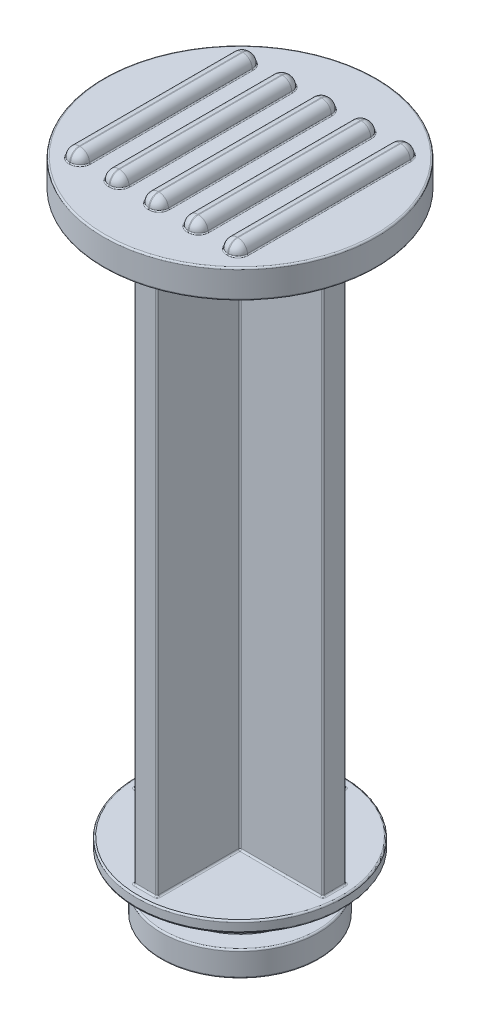
SolidWorks part; units mm, degrees
material "PET"
ref_plane "Front Plane" through (0, 0, 0) normal (0, 0, 1) x (1, 0, 0)
ref_plane "Top Plane" through (0, 0, 0) normal (0, 1, 0) x (1, 0, 0)
ref_plane "Right Plane" through (0, 0, 0) normal (1, 0, 0) x (0, 0, -1)
sketch "Main Body Sketch" plane through (0, 0, 0) normal (0, 0, 1) x (1, 0, 0)
  line L1 (-9, -26.665) -> (9, -26.665)
  line L2 (-9, -26.665) -> (-9, 26.665)
  line L3 (-9, 26.665) -> (9, 26.665)
  line L4 (9, -26.665) -> (9, 26.665)
  line L5 (-9, -26.665) -> (9, 26.665) construction
  line L6 (-9, 26.665) -> (9, -26.665) construction
  point P0 (0, 0)
  dimension "D1" = 53.33
  dimension "D2" = 18
extrude "Half Main Body Extrude" add sketch "Main Body Sketch" along normal mid plane 2.21 contours L3 L4 L1 L2
move or copy body "Half Main Body Copy" bodies to move or copy 101 copy yes number of copies 1 rotation origin (0, 0, 0) rotation axis (0, 1, 0) rotation angle 90 parameters "Pitch"=0, "Yaw"=90, "Roll"=0
sketch "Bottom Base Sketch" plane through (0, 26.665, 0) normal (0, 1, 0) x (1, 0, 0)
  circle A0 centre (0, 0) radius 13
  dimension "D1" = 26
extrude "Bottom Base Extrude" add sketch "Bottom Base Sketch" along normal blind 2.71
sketch "Protrusions Sketch" plane through (0, 29.375, 0) normal (0, 1, 0) x (1, 0, 0)
  line L1 (-0.94, -8.65) -> (0.94, -8.65)
  line L2 (-0.94, -8.65) -> (-0.94, 8.65)
  line L3 (-0.94, 8.65) -> (0.94, 8.65)
  line L4 (0.94, -8.65) -> (0.94, 8.65)
  line L5 (-0.94, -8.65) -> (0.94, 8.65) construction
  line L6 (-0.94, 8.65) -> (0.94, -8.65) construction
  point P0 (0, 0)
  dimension "D1" = 1.88
  dimension "D2" = 17.3
extrude "Protrusions Extrude" add sketch "Protrusions Sketch" along normal blind 0.97 contours L2 L1 L4 L3
fillet "Protrusions Smoothing" radius 0.9 8 edges at (0.94, 29.86, -8.65) (-0.94, 29.86, -8.65) (0, 30.345, -8.65) (0.94, 30.345, 0) (0.94, 29.86, 8.65) (0, 30.345, 8.65) (-0.94, 29.86, 8.65) (-0.94, 30.345, 0)
fillet "Protrusions Smoothing Platform" radius 0.1 8 edges at (0, 29.375, 8.65) (0, 29.375, -8.65) (0.6764, 29.375, -8.3864) (0.94, 29.375, 0) (0.6764, 29.375, 8.3864) (-0.6764, 29.375, -8.3864) (-0.6764, 29.375, 8.3864) (-0.94, 29.375, 0)
sketch "Orthogonal Protrusions Axis" plane through (0, 29.375, 0) normal (0, 1, 0) x (1, 0, 0)
  line L0 (-13, 0) -> (13, 0) construction
  circle A0 centre (0, 0) radius 13 construction
pattern_linear "LPattern1" count 3 spacing 3.76 along (1, 0, 0) count 3 spacing 3.76 along (-1, 0, 0) of "Protrusions Smoothing", "Protrusions Smoothing Platform", "Protrusions Extrude"
sketch "Top Base Sketch" plane through (0, -26.665, 0) normal (0, -1, 0) x (-1, 0, 0)
  circle A0 centre (0, 0) radius 9.875
  dimension "D1" = 19.75
extrude "Top Base Extrude" add sketch "Top Base Sketch" along normal blind 1.06 contours A0
sketch "Top Intermediate Sketch" plane through (0, -27.725, 0) normal (0, -1, 0) x (-1, 0, 0)
  circle A0 centre (0, 0) radius 5.7
  dimension "D1" = 11.4
extrude "Top Intermediate Base Extrude" add sketch "Top Intermediate Sketch" along normal blind 3 contours A0
sketch "Outer Base Sketch" plane through (0, -30.725, 0) normal (0, -1, 0) x (-1, 0, 0)
  circle A0 centre (0, 0) radius 7.505
  dimension "D1" = 15.01
extrude "Outer Base Extrude" add sketch "Outer Base Sketch" along normal blind 2.4
fillet "Smoothing Fillets" radius 0.15 42 edges at (9, 0, 1.105) (0, 26.665, 13) (0, 29.375, 13) (-5.0525, -26.665, 1.105) (5.0525, 26.665, -1.105) (5.0525, 26.665, 1.105) (-1.105, 26.665, -5.0525) (1.105, 26.665, -5.0525) (5.0525, -26.665, -1.105) (5.0525, -26.665, 1.105) (0, -26.665, -9.875) (0, -27.725, -9.875) (-1.105, -26.665, 5.0525) (0, -26.665, 9) (0, -30.725, -7.505) (1.105, 26.665, 5.0525) (0, -33.125, -7.505) (1.105, -26.665, 5.0525) (1.105, 0, 1.105) (1.105, 0, -1.105) (-1.105, 0, 9) (-1.105, 26.665, 5.0525) (-1.105, 0, 1.105) (1.105, 0, 9) (0, 26.665, 9) (-1.105, -26.665, -5.0525) (-1.105, 0, -9) (0, -26.665, -9) (0, 26.665, -9) (1.105, -26.665, -5.0525) (1.105, 0, -9) (-1.105, 0, -1.105) (-9, 0, 1.105) (-5.0525, -26.665, -1.105) (9, 0, -1.105) (-5.0525, 26.665, -1.105) (-9, 0, -1.105) (-9, -26.665, 0) (9, -26.665, 0) (9, 26.665, 0) (-9, 26.665, 0) (-5.0525, 26.665, 1.105)
